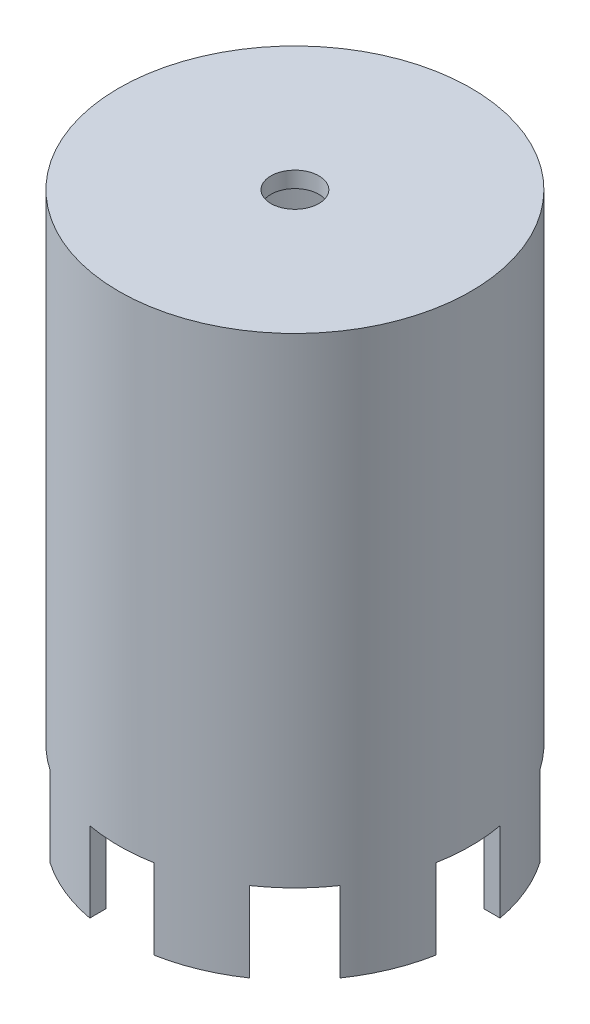
SolidWorks part; units mm, degrees
material "Copper"
ref_plane "Front Plane" through (0, 0, 0) normal (0, 0, 1) x (1, 0, 0)
ref_plane "Top Plane" through (0, 0, 0) normal (0, 1, 0) x (1, 0, 0)
ref_plane "Right Plane" through (0, 0, 0) normal (1, 0, 0) x (0, 0, -1)
sketch "Sketch1" plane through (0, 0, 0) normal (0, 1, 0) x (1, 0, 0)
  circle A0 centre (0, 0) radius 11
  dimension "D1" = 22
extrude "Boss-Extrude1" add sketch "Sketch1" along normal blind 35
ref_plane "Plane1" through (30, 0, 0) normal (1, 0, 0) x (0, 0, -1)
shell "Shell1" thickness 1
sketch "Sketch4" plane through (30, 0, 0) normal (1, 0, 0) x (0, 0, -1)
  line L0 (-11, 0) -> (11, 0) construction
  line L1 (-2, 0) -> (2, 0)
  line L2 (-2, 0) -> (-2, 5)
  line L3 (-2, 5) -> (2, 5)
  line L4 (2, 0) -> (2, 5)
  line L6 (0, 35) -> (0, 0) construction
  dimension "D1" = 5
  dimension "D2" = 4
  dimension "D3" = 2
extrude "Cut-Extrude1" cut sketch "Sketch4" against normal through all both and the other way through all
pattern_circular "CirPattern1" count 8 over 360 about axis through (0, 0, 0) along (0, 1, 0) of "Cut-Extrude1"
sketch "Sketch5" plane through (0, 35, 0) normal (0, 1, 0) x (1, 0, 0)
  circle A0 centre (0, 0) radius 1.5
  dimension "D1" = 3
extrude "Cut-Extrude2" cut sketch "Sketch5" against normal up to next
